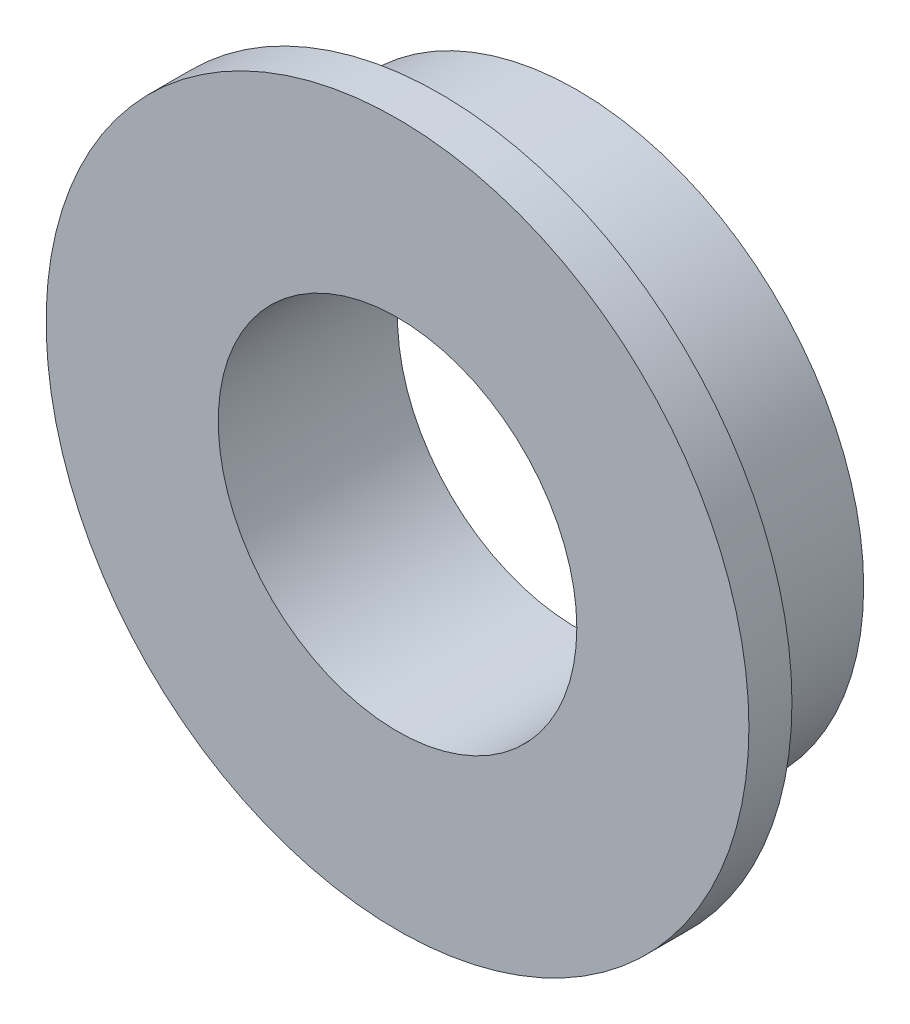
SolidWorks part; units mm, degrees
ref_plane "正面" through (0, 0, 0) normal (0, 0, 1) x (1, 0, 0)
ref_plane "平面" through (0, 0, 0) normal (0, 1, 0) x (1, 0, 0)
ref_plane "右側面" through (0, 0, 0) normal (1, 0, 0) x (0, 0, -1)
sketch "ｽｹｯﾁ2" plane through (0, 0, 0) normal (0, 0, 1) x (1, 0, 0)
  circle A0 centre (0, 0) radius 2.5
  circle A1 centre (0, 0) radius 4
  dimension "D1" = 8
  dimension "D2" = 5
extrude "ﾎﾞｽ - 押し出し1" add sketch "ｽｹｯﾁ2" along normal blind 2.5
sketch "ｽｹｯﾁ3" plane through (0, 0, 2.5) normal (0, 0, 1) x (1, 0, 0)
  circle A1 centre (0, 0) radius 4.9
  circle A2 centre (0, 0) radius 4
  circle A3 centre (0, 0) radius 4
  dimension "D2" = 9.8
  dimension "D1" = 0
extrude "ﾎﾞｽ - 押し出し2" add sketch "ｽｹｯﾁ3" against normal blind 0.6
